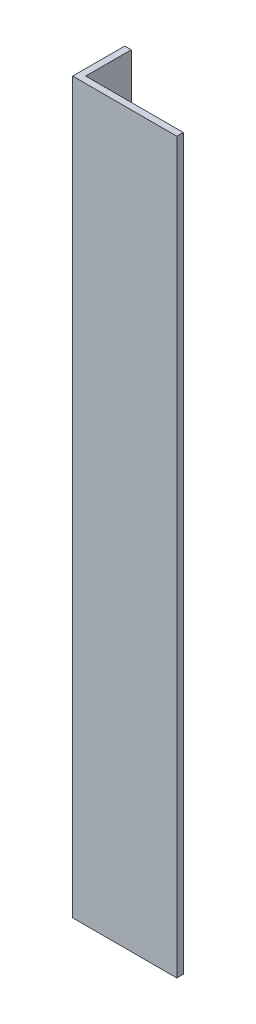
SolidWorks part; units mm, degrees
ref_plane "Front Plane" through (0, 0, 0) normal (0, 0, 1) x (1, 0, 0)
ref_plane "Top Plane" through (0, 0, 0) normal (0, 1, 0) x (1, 0, 0)
ref_plane "Right Plane" through (0, 0, 0) normal (1, 0, 0) x (0, 0, -1)
sketch "Sketch1" plane through (0, 0, 0) normal (0, 1, 0) x (1, 0, 0)
  line L0 (3.175, 3.175) -> (3.175, 25.4)
  line L1 (0, 0) -> (50.8, 0)
  line L2 (0, 0) -> (0, 25.4)
  line L5 (3.175, 3.175) -> (50.8, 3.175)
  line L6 (0, 25.4) -> (3.175, 25.4)
  line L7 (50.8, 0) -> (50.8, 3.175)
  dimension "D1" = 50.8
  dimension "D2" = 25.4
  dimension "D3" = 3.175
extrude "Boss-Extrude1" add sketch "Sketch1" along normal blind 355.6
